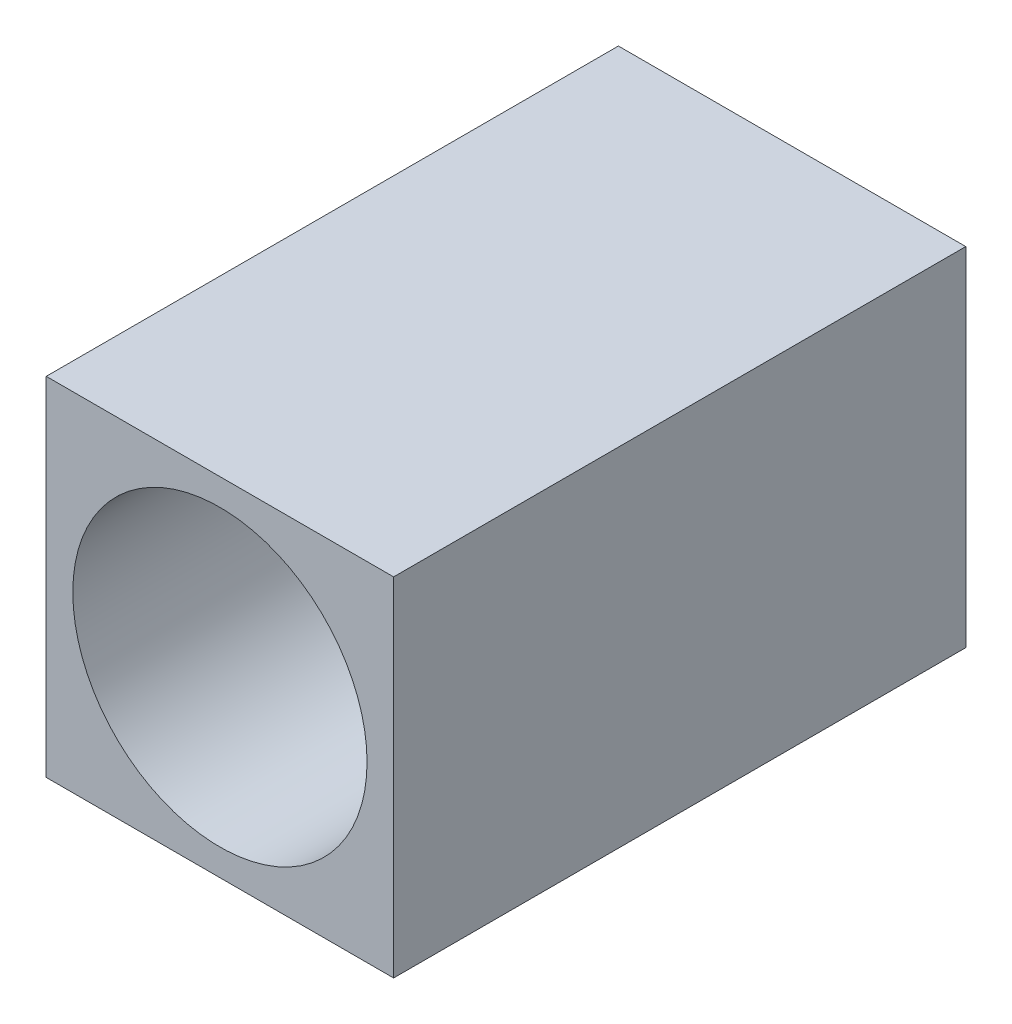
SolidWorks part; units mm, degrees
material "4032-T6"
ref_plane "正面" through (0, 0, 0) normal (0, 0, 1) x (1, 0, 0)
ref_plane "平面" through (0, 0, 0) normal (0, 1, 0) x (1, 0, 0)
ref_plane "右側面" through (0, 0, 0) normal (1, 0, 0) x (0, 0, -1)
sketch "ｽｹｯﾁ1" plane through (0, 0, 0) normal (0, 0, 1) x (1, 0, 0)
  line L1 (-42.5, 42.5) -> (42.5, 42.5)
  line L2 (-42.5, 42.5) -> (-42.5, -42.5)
  line L3 (-42.5, -42.5) -> (42.5, -42.5)
  line L4 (42.5, 42.5) -> (42.5, -42.5)
  line L5 (-42.5, 42.5) -> (42.5, -42.5) construction
  line L6 (-42.5, -42.5) -> (42.5, 42.5) construction
  circle A0 centre (0, 0) radius 36
  point P0 (0, 0)
  dimension "D3" = 72
  dimension "D1" = 85
  dimension "D2" = 85
extrude "ﾎﾞｽ - 押し出し1" add sketch "ｽｹｯﾁ1" along normal blind 140
